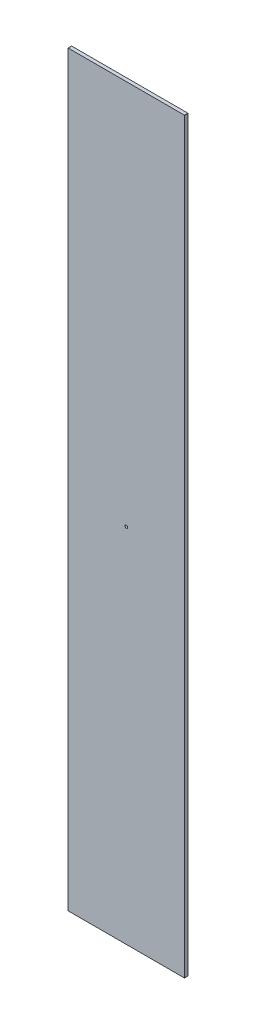
SolidWorks part; units mm, degrees
material "PE High Density"
ref_plane "Front Plane" through (0, 0, 0) normal (0, 0, 1) x (1, 0, 0)
ref_plane "Top Plane" through (0, 0, 0) normal (0, 1, 0) x (1, 0, 0)
ref_plane "Right Plane" through (0, 0, 0) normal (1, 0, 0) x (0, 0, -1)
sketch "Sketch1" plane through (0, 0, 0) normal (0, 0, 1) x (1, 0, 0)
  line L8 (-107.1708, 0) -> (107.1708, 0) construction
  line L15 (-107.1708, 591.8581) -> (107.1708, 591.8581)
  line L18 (-107.1708, -782.6375) -> (107.1708, -782.6375)
  line L21 (-107.1708, -782.6375) -> (-107.1708, 591.8581)
  line L22 (107.1708, -782.6375) -> (107.1708, 591.8581)
  point P0 (0, 0)
  point P2 (0, 0)
  dimension "D1" = 214.3416
  dimension "D2" = 1374.4956
extrude "Boss-Extrude1" add sketch "Sketch1" along normal blind 6.35
fillet "Fillet1" radius 0.254 4 edges at (107.1708, -782.6375, 3.175) (107.1708, 591.8581, 3.175) (-107.1708, 591.8581, 3.175) (-107.1708, -782.6375, 3.175)
sketch "Sketch2" plane through (0, 0, 6.35) normal (0, 0, 1) x (1, 0, 0)
  line L0 (-106.9168, -782.6375) -> (106.9168, -782.6375) construction
  circle A0 centre (0, -117.0813) radius 2.54
  dimension "D1" = 5.08
  dimension "D2" = 665.5562
extrude "Cut-Extrude1" cut sketch "Sketch2" against normal through all both and the other way through all
equation "\"D2@Sketch2\"=29+(0.1115*2)+0.02-0.04-3"
